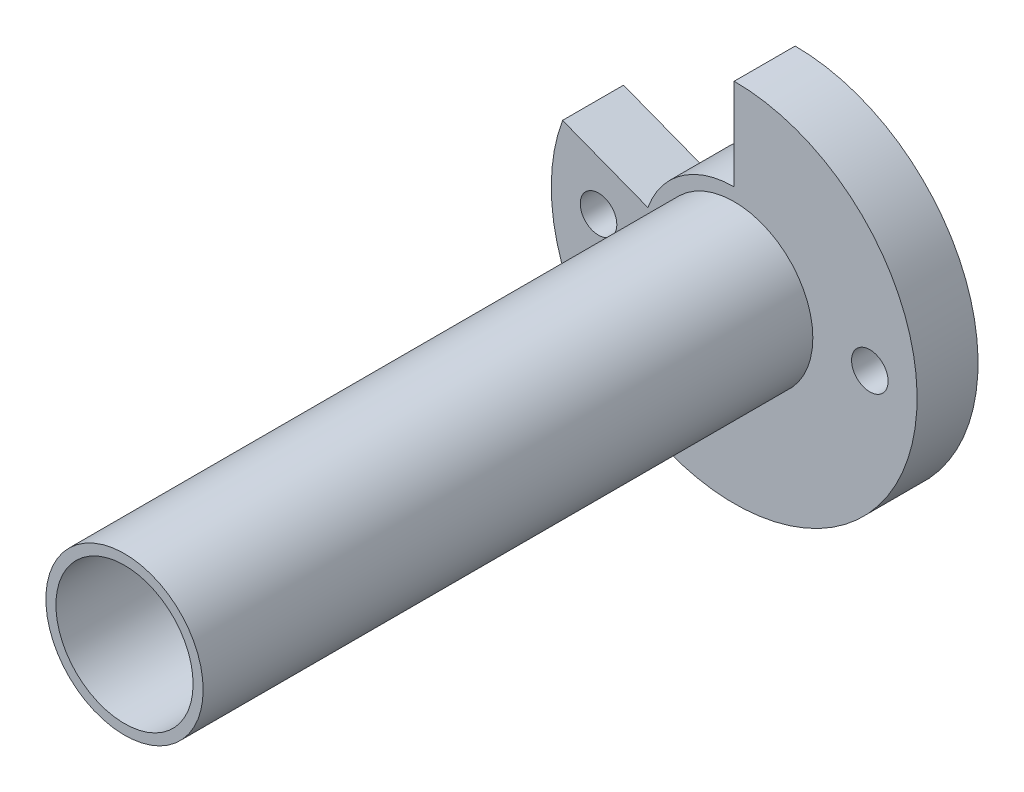
SolidWorks part; units mm, degrees
material "ABS"
ref_plane "Front Plane" through (0, 0, 0) normal (0, 0, 1) x (1, 0, 0)
ref_plane "Top Plane" through (0, 0, 0) normal (0, 1, 0) x (1, 0, 0)
ref_plane "Right Plane" through (0, 0, 0) normal (1, 0, 0) x (0, 0, -1)
sketch "Sketch1" plane through (0, 0, 0) normal (0, 0, 1) x (1, 0, 0)
  line L0 (0, 58.8693) -> (0, -36990.224) construction
  line L1 (-69.857, 0) -> (70.5717, 0) construction
  circle A0 centre (0, 0) radius 30
  dimension "D1" = 60
extrude "Boss-Extrude1" add sketch "Sketch1" along normal blind 10
sketch "Sketch2" plane through (0, 0, 10) normal (0, 0, 1) x (1, 0, 0)
  line L0 (0, 0) -> (0, 31.9031) construction
  line L1 (0, 0) -> (-48.7667, 0) construction
  circle A1 centre (0, 0) radius 12.9
  dimension "D1" = 25.8
extrude "Boss-Extrude2" add sketch "Sketch2" along normal blind 50
sketch "Sketch3" plane through (0, 0, 10) normal (0, 0, 1) x (1, 0, 0)
  line L0 (0, -0.5404) -> (0, 10.6724) construction
  line L1 (0.2768, 0) -> (-45.3304, 0) construction
  line L2 (-18.6599, -18.6599) -> (0, 0) construction
  arc A0 (22.25, 0) -> (-22.25, 0) centre (0, 0) ccw construction
  arc A1 (15, 0) -> (-15, 0) centre (0, 0) ccw construction
  arc A3 (22.25, 0) -> (-22.25, 0) centre (0, 0) cw construction
  point P4 (-22.25, 0)
  point P7 (22.25, 0)
  point P14 (0, 0)
  point P16 (15.7331, 15.7331)
  point P18 (-15.7331, -15.7331)
  dimension "D3" = 45
  dimension "D1" = 22.25
  dimension "D2" = 22.25
hole_wizard "Ø6.0mm Dowel Hole1" positions "Sketch5" profile "Sketch4" hole size "Ø6.0" standard "ANSI Metric" end condition up to next
sketch "Sketch5" plane through (0, 0, 10) normal (0, 0, 1) x (1, 0, 0)
  point P0 (-22.25, 0)
  point P3 (22.25, 0)
sketch "Sketch4" plane through (-22.25, 0, 10) normal (1, 0, 0) x (0, -1, 0)
  line L0 (0, 0) -> (0, 10)
  line L1 (0, 10) -> (3, 10)
  line L2 (3, 10) -> (3, 0)
  line L5 (3, 0) -> (0, 0)
  line L11 (0, -6.35) -> (0, 107.95) construction
  dimension "Thru Hole Dia." = 6
  dimension "Thru Hole Depth" = 10
sketch "Sketch7" plane through (0, 0, 10) normal (0, 0, 1) x (1, 0, 0)
  line L0 (0, -200000.5404) -> (0, 200010.6724) construction
  line L1 (0, 15) -> (0, 30)
  line L2 (-28.1521, 10.3663) -> (-14.1492, 4.9801)
  arc A0 (-14.1492, 4.9801) -> (0, 15) centre (0, 0) cw
  arc A1 (15, 0) -> (-15, 0) centre (0, 0) ccw construction
  circle A2 centre (0, 0) radius 30 construction
  arc A3 (0, 30) -> (-28.1521, 10.3663) centre (0, 0) ccw
extrude "Cut-Extrude2" cut sketch "Sketch7" against normal blind 50
sketch "Sketch12" plane through (0, 0, 0) normal (0, 0, -1) x (-1, 0, 0)
  arc A0 (-22.25, 0) -> (22.25, 0) centre (0, 0) ccw construction
  point P0 (-15.7331, 15.7331)
  point P1 (15.7331, -15.7331)
  point P3 (-15.7331, -15.7331)
hole_wizard "Ø2.5mm Dowel Hole1" positions "Sketch14" profile "Sketch13" hole size "Ø2.5" standard "ANSI Metric"
sketch "Sketch14" plane through (0, 0, 0) normal (0, 0, -1) x (-1, 0, 0)
  point P0 (-15.7331, 15.7331)
  point P3 (-15.7331, -15.7331)
  point P6 (15.7331, -15.7331)
sketch "Sketch13" plane through (15.7331, 15.7331, 0) normal (1, 0, 0) x (0, 1, 0)
  line L0 (0, 0) -> (0, 5)
  line L1 (0, 5) -> (1.25, 5)
  line L2 (1.25, 5) -> (1.25, 0)
  line L5 (1.25, 0) -> (0, 0)
  line L10 (0, 5) -> (-1.25, 5) construction
  line L11 (0, -6.35) -> (0, 107.95) construction
  dimension "Hole Dia." = 2.5
  dimension "Hole Depth" = 5
  dimension "Drill Angle" = 180
sketch "Sketch15" plane through (0, 0, 60) normal (0, 0, 1) x (1, 0, 0)
  circle A0 centre (0, 0) radius 12.9
  circle A1 centre (0, 0) radius 11.25
  dimension "D1" = 25.8
  dimension "D2" = 22.5
extrude "Boss-Extrude3" add sketch "Sketch15" along normal blind 50
hole_wizard "Ø6.0mm Dowel Hole2" positions "Sketch19" profile "Sketch18" hole size "Ø6.0" standard "ANSI Metric" end condition up to next
sketch "Sketch19" plane through (0, 0, 0) normal (0, 0, -1) x (-1, 0, 0)
  point P0 (0, 0)
sketch "Sketch18" plane through (0, 0, 0) normal (1, 0, 0) x (0, 1, 0)
  line L0 (0, 0) -> (0, 60)
  line L1 (0, 60) -> (10, 60)
  line L2 (10, 60) -> (10, 0)
  line L5 (10, 0) -> (0, 0)
  line L11 (0, -6.35) -> (0, 107.95) construction
  dimension "Thru Hole Dia." = 20
  dimension "Thru Hole Depth" = 60
